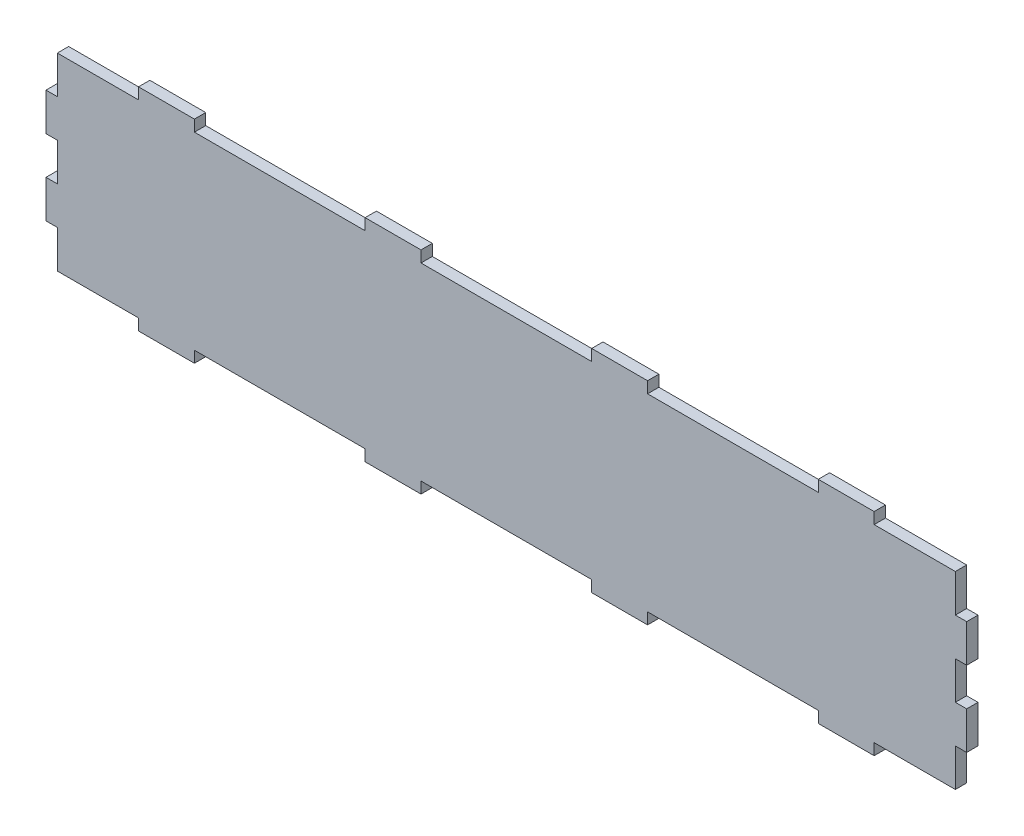
SolidWorks part; units mm, degrees
ref_plane "Front Plane" through (0, 0, 0) normal (0, 0, 1) x (1, 0, 0)
ref_plane "Top Plane" through (0, 0, 0) normal (0, 1, 0) x (1, 0, 0)
ref_plane "Right Plane" through (0, 0, 0) normal (1, 0, 0) x (0, 0, -1)
sketch "Sketch1" plane through (0, 0, 0) normal (0, 0, 1) x (1, 0, 0)
  line L0 (-22.6, 0) -> (22.6, 0)
  line L1 (118.9, 0) -> (118.9, -10)
  line L2 (118.9, -10) -> (121.9, -10)
  line L3 (121.9, -10) -> (121.9, -20)
  line L4 (121.9, -20) -> (118.9, -20)
  line L5 (118.9, -20) -> (118.9, -30)
  line L6 (118.9, -30) -> (121.9, -30)
  line L7 (121.9, -30) -> (121.9, -40)
  line L8 (121.9, -40) -> (118.9, -40)
  line L9 (118.9, -40) -> (118.9, -50)
  line L10 (-118.9, -25) -> (118.9, -25) construction
  line L11 (0, -50) -> (0, 0) construction
  line L12 (97.4, 0) -> (97.4, 3)
  line L13 (97.4, 3) -> (82.6, 3)
  line L14 (82.6, 3) -> (82.6, 0)
  line L15 (82.6, 0) -> (37.4, 0)
  line L16 (37.4, 0) -> (37.4, 3)
  line L17 (37.4, 3) -> (22.6, 3)
  line L18 (22.6, 3) -> (22.6, 0)
  line L19 (37.4, 0) -> (82.6, 0)
  line L20 (97.4, 0) -> (118.9, 0)
  line L21 (97.4, -50) -> (118.9, -50)
  line L22 (-22.6, -50) -> (22.6, -50)
  line L23 (37.4, -50) -> (82.6, -50)
  line L24 (22.6, -53) -> (22.6, -50)
  line L25 (37.4, -53) -> (22.6, -53)
  line L26 (37.4, -50) -> (37.4, -53)
  line L27 (82.6, -50) -> (37.4, -50)
  line L28 (82.6, -53) -> (82.6, -50)
  line L29 (97.4, -53) -> (82.6, -53)
  line L30 (97.4, -50) -> (97.4, -53)
  line L31 (-97.4, -50) -> (-97.4, -53)
  line L32 (-97.4, -53) -> (-82.6, -53)
  line L33 (-82.6, -53) -> (-82.6, -50)
  line L34 (-82.6, -50) -> (-37.4, -50)
  line L35 (-37.4, -50) -> (-37.4, -53)
  line L36 (-37.4, -53) -> (-22.6, -53)
  line L37 (-22.6, -53) -> (-22.6, -50)
  line L38 (-37.4, -50) -> (-82.6, -50)
  line L39 (-97.4, -50) -> (-118.9, -50)
  line L40 (-97.4, 0) -> (-118.9, 0)
  line L41 (-37.4, 0) -> (-82.6, 0)
  line L42 (-22.6, 3) -> (-22.6, 0)
  line L43 (-37.4, 3) -> (-22.6, 3)
  line L44 (-37.4, 0) -> (-37.4, 3)
  line L45 (-82.6, 0) -> (-37.4, 0)
  line L46 (-82.6, 3) -> (-82.6, 0)
  line L47 (-97.4, 3) -> (-82.6, 3)
  line L48 (-97.4, 0) -> (-97.4, 3)
  line L49 (-118.9, -40) -> (-118.9, -50)
  line L50 (-121.9, -40) -> (-118.9, -40)
  line L51 (-121.9, -30) -> (-121.9, -40)
  line L52 (-118.9, -30) -> (-121.9, -30)
  line L53 (-118.9, -20) -> (-118.9, -30)
  line L54 (-121.9, -20) -> (-118.9, -20)
  line L55 (-121.9, -10) -> (-121.9, -20)
  line L56 (-118.9, -10) -> (-121.9, -10)
  line L57 (-118.9, 0) -> (-118.9, -10)
  point P32 (0, -25)
  dimension "D1" = 118.9
  dimension "D2" = 10
  dimension "D3" = 3
  dimension "D4" = 14.8
  dimension "D5" = 3
  dimension "D6" = 21.5
  dimension "D7" = 45.2
extrude "Boss-Extrude1" add sketch "Sketch1" along normal blind 3 contours L40 L57 L56 L55 L54 L53 L52 L51 L50 L49 L39 L31 L32 L33 L34 L35 L36 L37 L22 L24 L25 L26 L23 L28 L29 L30 L21 L9 L8 L7 L6 L5 L4 L3 L2 L1 L20 L12 L13 L14 L15 L16 L17 L18 L0 L42 L43 L44 L41 L46 L47
